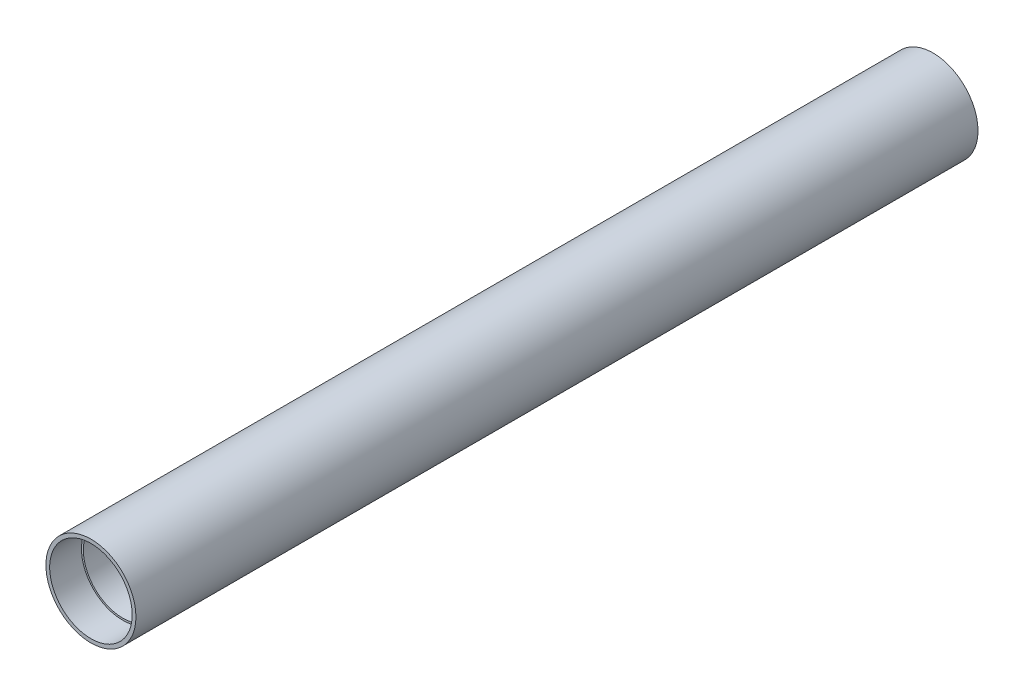
SolidWorks part; units mm, degrees
material "G-10 Fiberglass"
ref_plane "Front Plane" through (0, 0, 0) normal (0, 0, 1) x (1, 0, 0)
ref_plane "Top Plane" through (0, 0, 0) normal (0, 1, 0) x (1, 0, 0)
ref_plane "Right Plane" through (0, 0, 0) normal (1, 0, 0) x (0, 0, -1)
sketch "Sketch1" plane through (0, 0, 0) normal (0, 0, 1) x (1, 0, 0)
  circle A0 centre (0, 0) radius 19.05
  circle A1 centre (0, 0) radius 16.6751
  dimension "D1" = 38.1
  dimension "D2" = 33.3502
extrude "Boss-Extrude1" add sketch "Sketch1" along normal blind 356.362
sketch "Sketch2" plane through (0, 0, 356.362) normal (0, 0, 1) x (1, 0, 0)
  circle A0 centre (0, 0) radius 17.4625
  dimension "D1" = 34.925
extrude "Cut-Extrude1" cut sketch "Sketch2" against normal blind 13.462
sketch "Sketch3" plane through (0, 0, 0) normal (0, 0, -1) x (-1, 0, 0)
  circle A0 centre (0, 0) radius 17.4625
  circle A1 centre (0, 0) radius 17.4625 construction
extrude "Cut-Extrude2" cut sketch "Sketch3" against normal blind 13.462
equation "\"D1@Cut-Extrude2\"= \"D1@Cut-Extrude1\""
